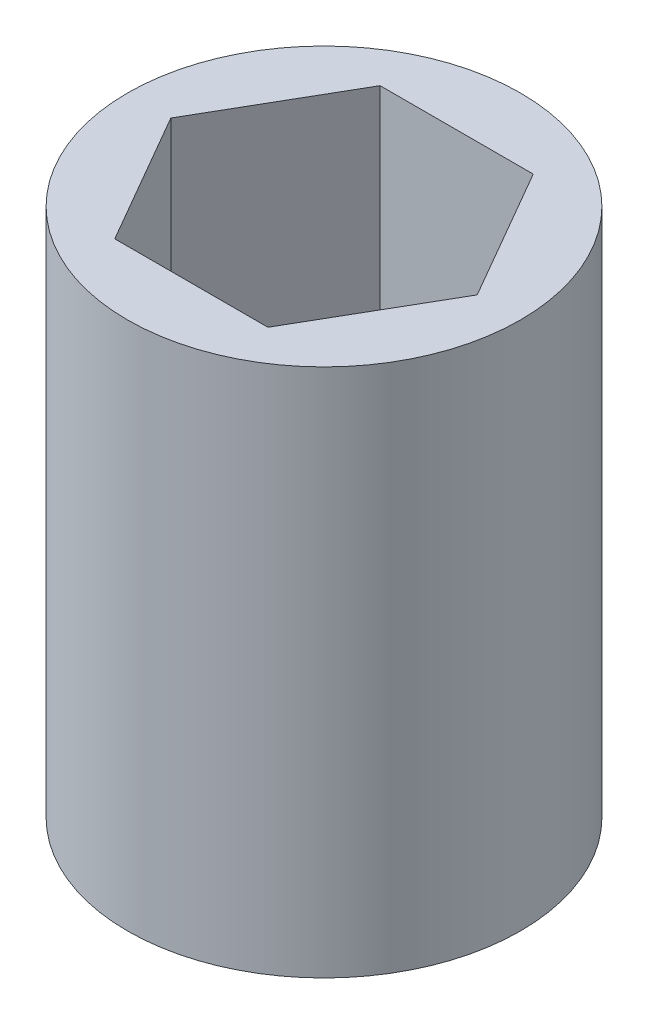
SolidWorks part; units mm, degrees
ref_plane "Front Plane" through (0, 0, 0) normal (0, 0, 1) x (1, 0, 0)
ref_plane "Top Plane" through (0, 0, 0) normal (0, 1, 0) x (1, 0, 0)
ref_plane "Right Plane" through (0, 0, 0) normal (1, 0, 0) x (0, 0, -1)
sketch "Sketch1" plane through (0, 0, 0) normal (0, 1, 0) x (1, 0, 0)
  line L1 (7.9189, 0) -> (3.9595, 6.858)
  line L2 (3.9595, 6.858) -> (-3.9595, 6.858)
  line L3 (-3.9595, 6.858) -> (-7.9189, 0)
  line L4 (-7.9189, 0) -> (-3.9595, -6.858)
  line L5 (-3.9595, -6.858) -> (3.9595, -6.858)
  line L6 (3.9595, -6.858) -> (7.9189, 0)
  circle A0 centre (0, 0) radius 6.858 construction
  circle A1 centre (0, 0) radius 10.16
  dimension "D2" = 20.32
  dimension "D1" = 13.716
extrude "Boss-Extrude1" add sketch "Sketch1" along normal blind 27.3583
